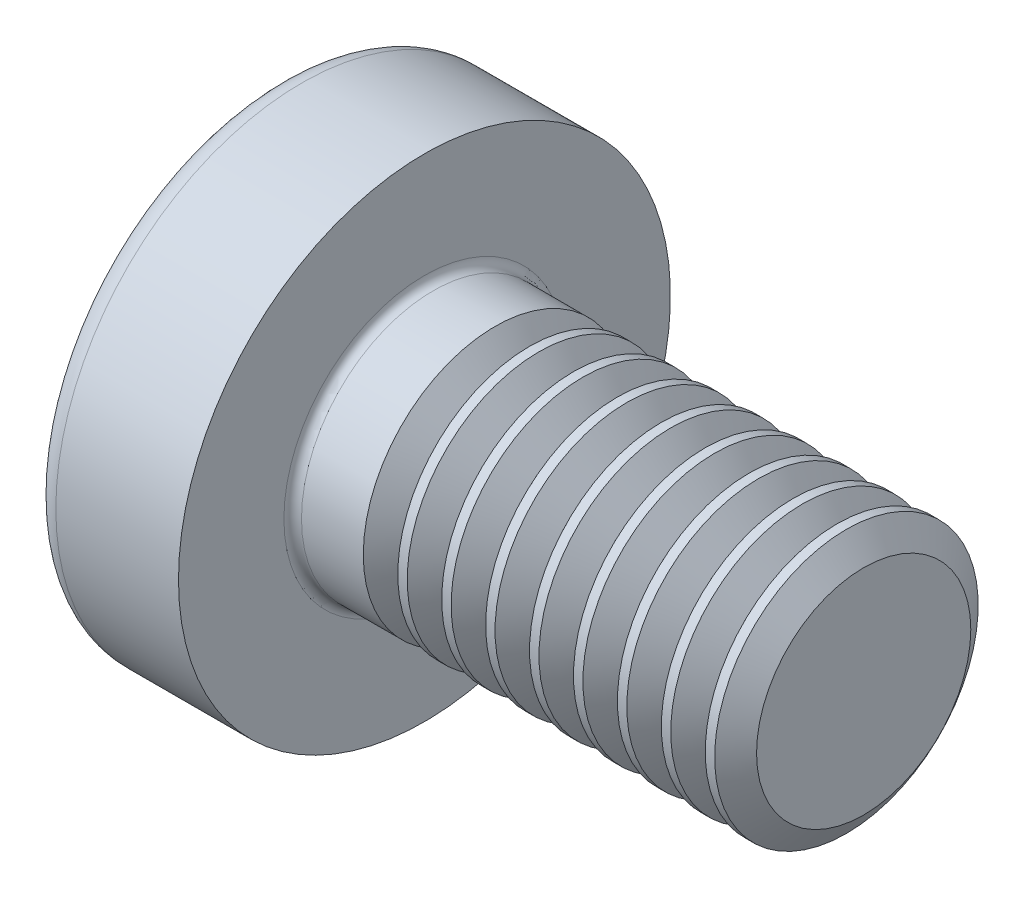
SolidWorks part; units mm, degrees
ref_plane "Plane1" through (0, 0, 0) normal (0, 0, 1) x (1, 0, 0)
ref_plane "Plane2" through (0, 0, 0) normal (0, 1, 0) x (1, 0, 0)
ref_plane "Plane3" through (0, 0, 0) normal (1, 0, 0) x (0, 0, -1)
sketch "BodySke" plane through (0, 0, 0) normal (0, 0, 1) x (1, 0, 0)
  line L0 (2.4, 1.5) -> (2.4, 2.8)
  line L1 (2.65, 6.35) -> (2.65, -3.175) construction
  line L2 (-25.4, 0) -> (127, 0) construction
  line L3 (7.4, 0) -> (0, 0)
  line L4 (2.4, 1.5) -> (7.4, 1.5)
  line L5 (7.4, 1.5) -> (7.4, 0)
  line L6 (1.0035, 2.8) -> (2.4, 2.8)
  line L8 (2.4, 6.35) -> (2.4, -3.175) construction
  arc A0 (0.7754, 2.6744) -> (0, 0) centre (5, 0) ccw
  arc A2 (0.7754, 2.6744) -> (1.0035, 2.8) centre (1.0035, 2.53) cw
  dimension "Head_crown_rad" = 5
  dimension "Head_fillet_rad" = 0.27
  dimension "Length" = 5
  dimension "Head_ht" = 2.4
  dimension "Head_dia" = 5.6
  dimension "Advance" = 0.5
  dimension "Thread_nom" = 5
  dimension "Diameter" = 3
revolve "Base-Revolve" add sketch "BodySke"
cosmetic thread "ThreadCosmetic" [suppressed]
fillet "Fillet1" radius 0.1 1 edges at (2.4, 0, 1.5)
sketch "Sketch3" plane through (0, 0, 0) normal (1, 0, 0) x (0, 0, -1)
  line L0 (0.37, -1.4) -> (-0.37, -1.4)
  line L1 (0.37, -1.4) -> (0.37, 1.4)
  line L2 (-0.37, 1.4) -> (0.37, 1.4)
  line L3 (-0.37, 1.4) -> (-0.37, -1.4)
  dimension "Cross_dia" = 2.8
  dimension "D1" = 1.4
  dimension "Cross_width" = 0.74
  dimension "D2" = 0.37
ref_plane "Plane4" through (1.75, 0, 0) normal (1, 0, 0) x (0, 0, -1)
sketch "Sketch4" plane through (1.75, 0, 0) normal (1, 0, 0) x (0, 0, -1)
  line L0 (0.37, -0.5275) -> (-0.37, -0.5275)
  line L1 (0.37, -0.5275) -> (0.37, 0.5275)
  line L2 (-0.37, 0.5275) -> (0.37, 0.5275)
  line L3 (-0.37, 0.5275) -> (-0.37, -0.5275)
  dimension "D1" = 0.74
  dimension "D2" = 1.055
  dimension "D3" = 0.37
  dimension "D4" = 0.5275
loft "Recess" cut profiles "Sketch3", "Sketch4"
pattern_circular "RecPat" count 2 every 90 about axis through (0, 0, 0) along (1, 0, 0) of "Recess"
sketch "RecCorSke" plane through (0, 0, 0) normal (0, 0, 1) x (1, 0, 0)
  line L0 (-3.175, 0) -> (15.875, 0) construction
  line L1 (-25.4, 0) -> (127, 0) construction
  line L2 (0, 0) -> (0, 0.6784)
  line L3 (0, 0.6784) -> (1.75, 0.556)
  line L4 (1.75, 0.556) -> (1.9307, 0)
  line L5 (1.9307, 0) -> (0, 0)
  dimension "Diameter" = 1.112
  dimension "Depth" = 1.75
  dimension "Draft_angle" = 4
  dimension "Bottom_angle" = 18
revolve "RecessCore" cut sketch "RecCorSke" angle 360 about L0
sketch "ThdSchSke" plane through (0, 0, 0) normal (0, 0, 1) x (1, 0, 0)
  line L0 (3.4, -1.2195) -> (3.2036, -1.5)
  line L1 (3.4, -1.2195) -> (3.5964, -1.5)
  line L2 (3.5964, -1.5) -> (3.5964, -1.875)
  line L3 (-3.175, 0) -> (5.1513, 0) construction
  line L5 (3.5964, -1.875) -> (3.2036, -1.875)
  line L6 (3.2036, -1.875) -> (3.2036, -1.5)
  dimension "Diameter" = 3
  dimension "SideAngle" = 55
  dimension "VeeAngle" = 70
  dimension "Thread_minor" = 2.439
  dimension "Overcut" = 3.75
  dimension "Start" = 3.4
revolve "ThreadSchematic" cut sketch "ThdSchSke" angle 360 about L3
pattern_linear "ThdSchPat" count 9 spacing 0.5 along (1, 0, 0) of "ThreadSchematic"
equation "\"D1@Sketch3\" = \"Cross_dia@Sketch3\" / 2"
equation "\"D2@Sketch3\" = \"Cross_width@Sketch3\" / 2"
equation "\"Depth@RecCorSke\" = \"Cross_depth@Plane4\""
equation "\"D1@Sketch4\" = \"Cross_width@Sketch3\""
equation "\"D2@Sketch4\" = \"Cross_dia@Sketch3\" - 2.0 * \"Cross_depth@Plane4\" * tan(26.5  * 0.017453292)"
equation "\"D3@Sketch4\" = \"D1@Sketch4\" / 2"
equation "\"D4@Sketch4\" = \"D2@Sketch4\" / 2"
equation "\"Thread_length@ThreadCosmetic\" = ((sgn( (\"Length@BodySke\" - \"Advance@BodySke\" * 2.0 ) - \"Thread_nom@BodySke\" )-1)*( (\"Length@BodySke\" - \"Advance@BodySke\" * 2.0 ) - \"Thread_nom@BodySke\" ))/-2+ \"Thread_nom@BodySke\""
equation "\"Thread_minor@ThdSchSke\" = \"Thread_minor@ThreadCosmetic\""
equation "\"Diameter@ThdSchSke\" = \"Diameter@BodySke\""
equation "\"Overcut@ThdSchSke\" = \"Diameter@BodySke\" * 1.25"
equation "\"Start@ThdSchSke\" = \"Head_ht@BodySke\" + \"Length@BodySke\" - \"Thread_length@ThreadCosmetic\"  '---Non-countersunk---"
equation "\"Num_threads@ThdSchPat\" = int( \"Thread_length@ThreadCosmetic\" / \"Advance@BodySke\" + 0.999 )  + 1"
equation "\"Advance@ThdSchPat\" = \"Thread_length@ThreadCosmetic\" /  (\"Num_threads@ThdSchPat\" - 1) 'relax it"
